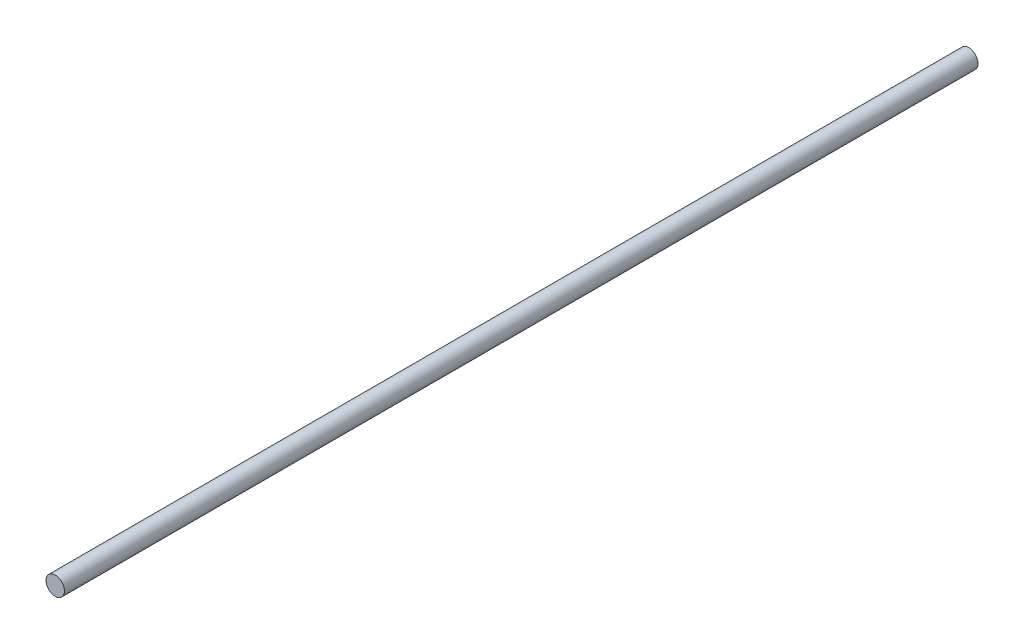
SolidWorks part; units mm, degrees
ref_plane "Front Plane" through (0, 0, 0) normal (0, 0, 1) x (1, 0, 0)
ref_plane "Top Plane" through (0, 0, 0) normal (0, 1, 0) x (1, 0, 0)
ref_plane "Right Plane" through (0, 0, 0) normal (1, 0, 0) x (0, 0, -1)
sketch "Sketch1" plane through (0, 0, 0) normal (0, 0, 1) x (1, 0, 0)
  circle A0 centre (0, 0) radius 5
  dimension "D1" = 10
extrude "Boss-Extrude1" add sketch "Sketch1" along normal blind 495
